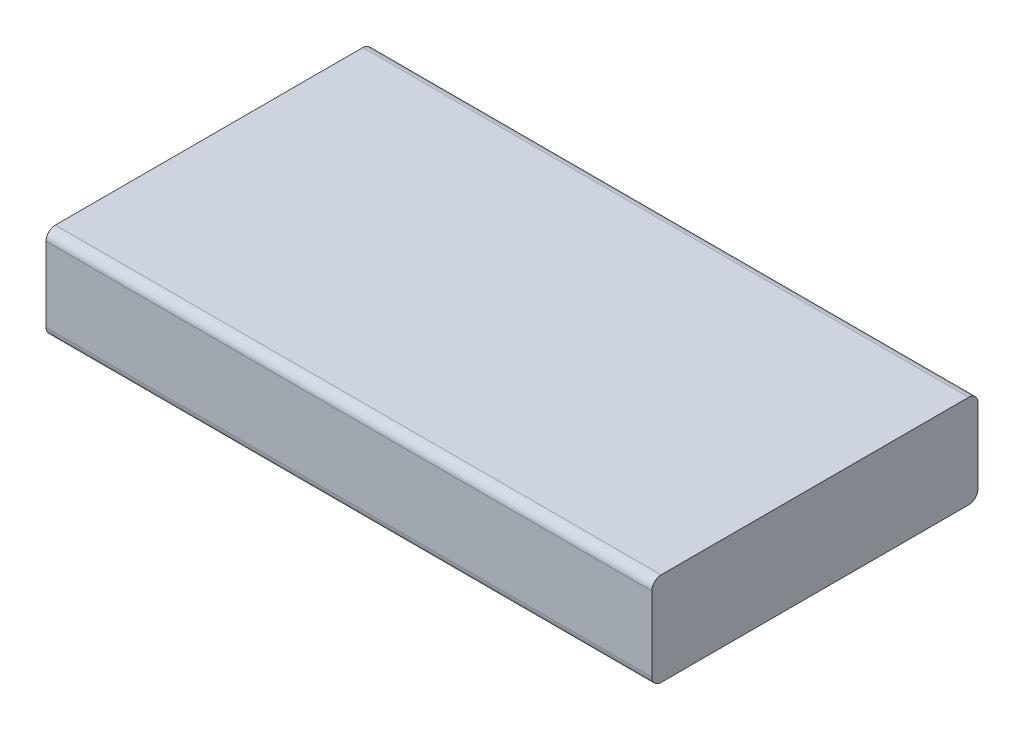
SolidWorks part; units mm, degrees
ref_plane "Plano frontal" through (0, 0, 0) normal (0, 0, 1) x (1, 0, 0)
ref_plane "Plano superior" through (0, 0, 0) normal (0, 1, 0) x (1, 0, 0)
ref_plane "Plano direito" through (0, 0, 0) normal (1, 0, 0) x (0, 0, -1)
sketch "Esboço1" plane through (0, 0, 0) normal (1, 0, 0) x (0, 0, -1)
  line L1 (0, 0) -> (35, 0)
  line L2 (0, 0) -> (0, 10)
  line L3 (0, 10) -> (35, 10)
  line L4 (35, 0) -> (35, 10)
  dimension "D1" = 10
  dimension "D2" = 35
extrude "Ressalto-extrusão1" add sketch "Esboço1" along normal blind 65
fillet "Filete2" radius 1 4 edges at (32.5, 0, -35) (32.5, 0, 0) (32.5, 10, -35) (32.5, 10, 0)
